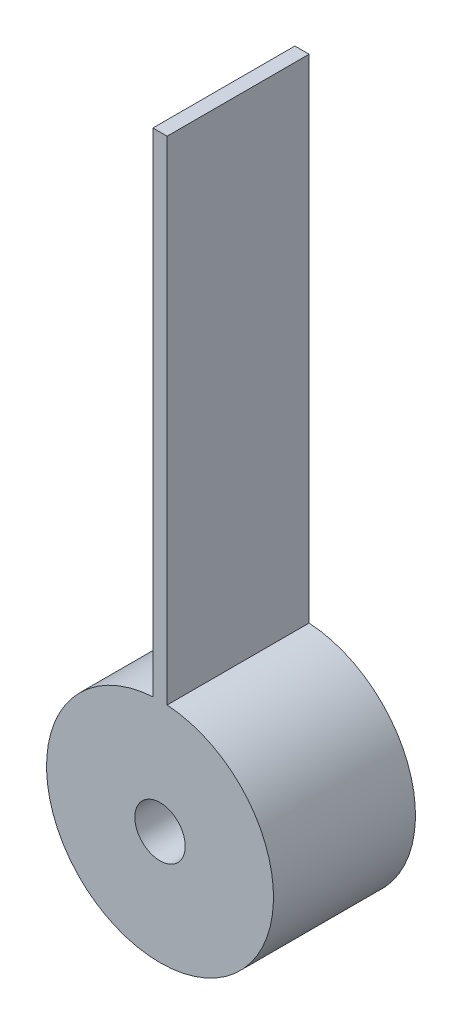
SolidWorks part; units mm, degrees
ref_plane "前视基准面" through (0, 0, 0) normal (0, 0, 1) x (1, 0, 0)
ref_plane "上视基准面" through (0, 0, 0) normal (0, 1, 0) x (1, 0, 0)
ref_plane "右视基准面" through (0, 0, 0) normal (1, 0, 0) x (0, 0, -1)
sketch "Model" plane through (0, 0, 0) normal (0, 0, 1) x (1, 0, 0)
  line L0 (98.576, 107.4567) -> (109.2328, 107.4567)
  line L1 (104.6851, 111.1897) -> (106.5119, 107.4567)
  line L2 (103.1237, 111.1897) -> (101.2969, 107.4567)
  line L3 (84.8109, 167.8456) -> (84.8109, 160.741)
  line L4 (84.8109, 160.741) -> (82.1466, 160.741)
  line L5 (84.8109, 167.8456) -> (82.1466, 167.8456)
  line L6 (87.4751, 167.8456) -> (87.4751, 160.741)
  line L7 (87.4751, 160.741) -> (90.1393, 160.741)
  line L8 (87.4751, 167.8456) -> (90.1393, 167.8456)
  line L9 (98.576, 107.0039) -> (99.0288, 107.4567)
  line L10 (98.576, 105.0101) -> (101.0225, 107.4567)
  line L11 (100.3521, 104.7925) -> (103.0163, 107.4567)
  line L12 (102.3459, 104.7925) -> (105.0101, 107.4567)
  line L13 (104.3397, 104.7925) -> (107.0039, 107.4567)
  line L14 (106.3334, 104.7925) -> (108.9977, 107.4567)
  line L15 (82.1466, 166.3381) -> (83.6541, 167.8456)
  line L16 (82.1466, 164.3443) -> (84.8109, 167.0085)
  line L17 (82.1466, 162.3506) -> (84.8109, 165.0148)
  line L18 (82.5308, 160.741) -> (84.8109, 163.021)
  line L19 (84.5246, 160.741) -> (84.8109, 161.0272)
  line L20 (87.4751, 167.679) -> (87.6416, 167.8456)
  line L21 (87.4751, 165.6852) -> (89.6354, 167.8456)
  line L22 (87.4751, 163.6914) -> (90.1393, 166.3556)
  line L23 (87.4751, 161.6977) -> (90.1393, 164.3619)
  line L24 (88.5122, 160.741) -> (90.1393, 162.3681)
  line L25 (86.143, 137.1587) -> (86.143, 178.0584)
  line L26 (86.143, 178.0584) -> (85.643, 178.0584)
  line L27 (86.143, 178.0584) -> (86.643, 178.0584)
  line L28 (85.643, 178.0584) -> (85.643, 143.3595)
  line L29 (86.643, 178.0584) -> (86.643, 143.3595)
  circle A0 centre (103.9044, 112.7851) radius 1.7761
  circle A1 centre (86.143, 135.3826) radius 7.9926
  circle A2 centre (86.143, 135.3826) radius 1.7761
  arc A3 (108.9107, 119.2638) -> (96.8478, 116.9374) centre (103.9044, 112.7851) ccw
  arc A4 (99.2234, 119.5026) -> (96.8478, 116.9374) centre (103.9044, 112.7851) ccw
  spline S0 degree 3 poles (87.8153, 127.3728) (91.6519, 129.09) (95.5025, 130.8246) (99.8156, 132.1638) (103.5377, 132.5082) (106.6862, 132.6656) (110.229, 132.3961) (113.8975, 131.1403) (117.8457, 128.7534) (121.6231, 125.4243) (125.6785, 120.5) (130.2984, 114.1306) (134.0269, 106.8865) (135.6212, 101.4647) (136.7682, 97.7963) (137.397, 94.167) (137.3579, 89.314) (136.4473, 83.5323) (133.3741, 77.6482) (129.0452, 72.2789) (125.0833, 68.3865) (121.3398, 66.1034) (117.6497, 64.9583) (113.6067, 64.0065) (108.9974, 63.4117) (104.3061, 63.3824) (99.5847, 63.6057) (95.1021, 64.1854) (90.7946, 64.9972) (86.6995, 66.6143) (83.4359, 68.3905) (80.3418, 70.0499) (76.8669, 72.541) (73.0704, 75.6567) (69.8007, 79.9865) (66.2492, 84.636) (65.3028, 91.2762) (65.851, 97.5635) (66.4795, 103.5965) (67.0332, 108.6575) (68.9157, 113.0833) (70.1566, 116.8633) (72.778, 119.1315) (74.8675, 121.1643) (77.2797, 122.3392) (80.3246, 124.2291) (84.1579, 125.8508) (87.8153, 127.3728) (91.6519, 129.09) (95.5025, 130.8246) knots -0.053528 -0.030186 -0.010705 0 0.026546 0.046329 0.060553 0.076868 0.088874 0.108295 0.128518 0.150854 0.175898 0.214483 0.256993 0.284989 0.290659 0.308876 0.334401 0.35592 0.38726 0.422471 0.449005 0.461679 0.481274 0.500786 0.517775 0.543869 0.564008 0.581536 0.604881 0.622946 0.640688 0.655045 0.670269 0.698381 0.72078 0.743531 0.77623 0.807771 0.829063 0.85826 0.875615 0.89409 0.910614 0.921398 0.933329 0.946472 0.969814 0.989295 1 1.026546 1.046329 1.060553 only from (90.5803, 128.611) to (90.5803, 128.611)
  spline S1 degree 3 poles (115.1837, 56.2408) (114.5241, 56.1179) (113.8567, 56.0082) (112.5215, 55.8179) (111.8517, 55.737) (110.5434, 55.6073) (109.9033, 55.5573) (108.6447, 55.4828) (108.0235, 55.4577) (106.1857, 55.4112) (104.9946, 55.4181) (103.3546, 55.4547) (102.8698, 55.4689) (101.8872, 55.5059) (100.7921, 55.5566) (99.6755, 55.6337) (98.6085, 55.7239) (98.1561, 55.7674) (97.2631, 55.8628) (96.3316, 55.9725) (95.4159, 56.0987) (94.4434, 56.2415) (93.9543, 56.3175) (92.9406, 56.4862) (92.4215, 56.5786) (90.8301, 56.8896) (89.7232, 57.1418) (88.1662, 57.5889) (87.7468, 57.7184) (86.9269, 57.9895) (86.5229, 58.132) (85.3284, 58.5775) (84.5556, 58.8986) (83.4175, 59.413) (83.0346, 59.5939) (82.2989, 59.9535) (81.9437, 60.133) (80.913, 60.6653) (80.2725, 61.0111) (79.4606, 61.4495) (79.2559, 61.5599) (78.8233, 61.7937) (78.5995, 61.915) (77.9066, 62.2948) (77.4162, 62.5689) (76.4534, 63.1371) (75.9786, 63.4313) (75.0881, 64.0128) (74.6624, 64.3046) (73.8303, 64.8936) (73.4251, 65.1906) (72.825, 65.6393) (72.618, 65.7956) (72.1968, 66.1174) (71.5606, 66.6089) (70.9134, 67.1296) (69.6115, 68.2164) (68.7329, 69.0016) (67.5914, 70.1427) (67.3162, 70.4273) (66.776, 71.008) (66.5177, 71.2966) (65.7738, 72.1528) (65.3192, 72.7105) (64.485, 73.7664) (64.1035, 74.266) (63.6418, 74.8733) (63.5422, 75.0045) (63.2479, 75.3919) (63.0392, 75.6663) (62.407, 76.5103) (61.9568, 77.1251) (61.0304, 78.5155) (60.5536, 79.2922) (59.8988, 80.5666) (59.6989, 80.9893) (59.3395, 81.8244) (59.1767, 82.2413) (58.7342, 83.4858) (58.4999, 84.3068) (57.9096, 86.8406) (57.7188, 88.4946) (57.5854, 90.8794) (57.5693, 91.6818) (57.5774, 93.2473) (57.6022, 94.0077) (57.687, 95.6677) (57.7543, 96.5546) (57.8769, 97.9644) (57.9284, 98.5066) (58.0824, 100.0917) (58.189, 101.1397) (58.3536, 102.7184) (58.4096, 103.2492) (58.5104, 104.1971) (58.5562, 104.6275) (58.6579, 105.5269) (58.7137, 105.9935) (58.9065, 107.4417) (59.0686, 108.4721) (59.3941, 109.9847) (59.5538, 110.6599) (59.7471, 111.3538) (59.8825, 111.812) (59.9466, 112.0191) (60.0749, 112.4173) (60.1396, 112.6104) (60.3333, 113.1724) (60.4621, 113.5239) (60.7016, 114.1601) (60.813, 114.4477) (60.9997, 114.9272) (61.0775, 115.126) (61.2975, 115.693) (61.4133, 116.0018) (61.7236, 116.8399) (61.9075, 117.3383) (62.3761, 118.4773) (62.6612, 119.1192) (63.1864, 120.0978) (63.3517, 120.3872) (63.6444, 120.8612) (63.7606, 121.0415) (63.9874, 121.3763) (64.0944, 121.5281) (64.3063, 121.8178) (64.4123, 121.9574) (64.729, 122.3615) (64.9384, 122.611) (65.5515, 123.3074) (65.9396, 123.7022) (66.6429, 124.3876) (66.9586, 124.6785) (67.3277, 125.0183) (67.4203, 125.1034) (67.5918, 125.2618) (67.6674, 125.332) (67.9406, 125.5869) (68.1629, 125.7963) (68.6066, 126.1994) (68.8052, 126.3764) (69.3151, 126.8113) (69.6423, 127.0774) (70.1779, 127.4736) (70.3521, 127.5973) (70.6838, 127.8235) (70.8449, 127.929) (71.3121, 128.2253) (71.6018, 128.3962) (72.1972, 128.7349) (72.4887, 128.8914) (72.9151, 129.1195) (73.071, 129.2025) (73.2901, 129.321) (73.363, 129.361) (73.5223, 129.4496) (73.6056, 129.4965) (73.8666, 129.6452) (74.0555, 129.7548) (74.6688, 130.1123) (75.1397, 130.3895) (75.8661, 130.7918) (76.0586, 130.8962) (76.435, 131.0958) (76.9961, 131.3868) (77.5454, 131.6549) (78.6251, 132.1655) (79.3199, 132.4722) (80.4305, 132.9491) (80.8634, 133.1311) (82.115, 133.656) (82.9267, 133.9947) (84.1792, 134.5258) (84.6324, 134.7198) (85.4087, 135.0575) (85.7398, 135.2035) (86.4805, 135.5324) (86.8904, 135.716) (87.308, 135.9031) knots 124.95846 124.95846 124.95846 124.95846 126.851625 126.851625 128.74479 128.74479 130.540216 130.540216 132.335642 132.335642 135.926493 135.926493 137.432557 137.432557 138.93862 140.758492 140.758492 142.085094 142.085094 143.411695 144.875502 144.875502 146.401689 146.401689 147.927876 147.927876 150.98025 150.98025 152.088003 152.088003 153.195757 153.195757 155.411264 155.411264 156.557338 156.557338 157.703412 157.703412 159.995561 159.995561 160.80138 160.80138 161.607198 161.607198 163.218836 163.218836 164.626323 164.626323 166.03381 166.03381 167.493852 167.493852 168.286348 168.286348 169.078843 170.663834 170.663834 173.833815 173.833815 174.840372 174.840372 175.846929 175.846929 177.860043 177.860043 179.81116 179.81116 180.359658 180.359658 181.456653 181.456653 183.521816 183.521816 185.586979 185.586979 186.519725 186.519725 187.45247 187.45247 189.317962 189.317962 193.324578 193.324578 195.476707 195.476707 197.628836 197.628836 200.317475 200.317475 202.071935 202.071935 205.580854 205.580854 207.361877 207.361877 208.763109 208.763109 210.164341 210.164341 212.966804 212.966804 214.063329 214.67253 214.67253 215.180192 215.180192 215.687854 215.687854 216.703178 216.703178 217.644549 217.644549 218.372655 218.372655 219.828867 219.828867 221.285079 221.285079 222.741291 222.741291 223.326665 223.326665 223.678609 223.678609 223.974426 223.974426 224.270244 224.270244 224.86188 224.86188 226.045151 226.045151 227.228422 227.228422 227.659654 227.659654 228.08589 228.08589 228.993858 228.993858 229.609088 229.609088 230.414166 230.414166 230.766752 230.766752 231.119337 231.119337 231.824508 231.824508 232.706509 232.706509 233.340309 233.340309 233.753263 233.753263 234.166216 234.166216 234.992124 234.992124 236.643938 236.643938 237.203236 237.203236 237.762535 238.881131 238.881131 241.118325 241.118325 242.624871 242.624871 245.637965 245.637965 247.38835 247.38835 248.685938 248.685938 250.231645 250.231645 250.231645 250.231645
  spline S2 degree 3 poles (87.308, 135.9031) (87.7349, 136.095) (88.1714, 136.2912) (89.5122, 136.8876) (90.4476, 137.2955) (92.0832, 137.9618) (92.7537, 138.2232) (94.1512, 138.731) (94.8867, 138.9802) (96.3938, 139.4303) (97.1613, 139.6331) (98.5103, 139.9236) (99.0819, 140.0274) (100.161, 140.1904) (100.6775, 140.2529) (101.7229, 140.3611) (102.2454, 140.4036) (103.0155, 140.4602) (103.2958, 140.4796) (103.8727, 140.5154) (104.167, 140.5317) (105.0677, 140.5735) (105.692, 140.5918) (106.9043, 140.594) (107.4842, 140.5826) (108.5756, 140.5255) (109.074, 140.4874) (109.9481, 140.3916) (110.3154, 140.3433) (110.9984, 140.2352) (111.3126, 140.1785) (111.9266, 140.0539) (112.2294, 139.9857) (113.1253, 139.765) (113.7056, 139.5966) (115.1371, 139.1256) (115.9653, 138.8) (117.4894, 138.1202) (118.1943, 137.7685) (119.5619, 137.0198) (120.2224, 136.6237) (122.1363, 135.3836) (123.3216, 134.4898) (125.1216, 132.9625) (125.7794, 132.3613) (126.9163, 131.2516) (127.406, 130.7466) (128.3377, 129.741) (128.7821, 129.2386) (129.6678, 128.2028) (130.1064, 127.6701) (130.8325, 126.7668) (131.1267, 126.3943) (131.7069, 125.6515) (132.5748, 124.5271) (133.4318, 123.3698) (135.1217, 121.0052) (136.2176, 119.3599) (138.2839, 115.915) (139.2525, 114.1202) (140.5148, 111.4214) (140.8841, 110.5774) (141.5213, 109.0045) (141.7971, 108.2731) (142.2986, 106.8565) (142.528, 106.1655) (142.903, 104.9965) (143.1525, 104.1971) (143.3882, 103.4296) (143.5963, 102.7519) (143.7037, 102.4035) (143.8899, 101.8015) (143.9571, 101.5833) (144.0769, 101.1792) (144.1279, 101.0036) (144.2879, 100.4289) (144.387, 100.0401) (144.6587, 98.8778) (144.8054, 98.1081) (145.1087, 96.1434) (145.2226, 94.9641) (145.3394, 92.6258) (145.3409, 91.4695) (145.2741, 89.818) (145.2438, 89.3098) (145.1731, 88.396) (145.1361, 87.9903) (145.0472, 87.1599) (144.9955, 86.7381) (144.8134, 85.4544) (144.6562, 84.5739) (144.3464, 83.2304) (144.232, 82.7825) (144.0108, 82.0058) (143.9109, 81.6795) (143.702, 81.0407) (143.5923, 80.7261) (143.2498, 79.7962) (143.0033, 79.1952) (142.2226, 77.4465) (141.6477, 76.3533) (140.7247, 74.771) (140.3947, 74.2365) (139.3932, 72.6843) (138.6936, 71.6921) (137.4505, 70.0522) (136.4479, 68.797) (135.4122, 67.6056) (134.6014, 66.7044) (134.2833, 66.3581) (133.618, 65.651) (133.2723, 65.2925) (132.1904, 64.2092) (131.4091, 63.4763) (129.9827, 62.2803) (129.3809, 61.8101) (128.2645, 61.0159) (127.3209, 60.3891) (126.2997, 59.8092) (125.4513, 59.3686) (125.0925, 59.194) (124.3891, 58.8736) (124.0422, 58.7261) (123.0192, 58.3157) (122.3612, 58.085) (121.2805, 57.7374) (120.8432, 57.6067) (120.1735, 57.4154) (119.9309, 57.3482) (119.4545, 57.2187) (118.7358, 57.0273) (117.2527, 56.6596) (115.974, 56.3879) (115.1837, 56.2408) knots 0.006287 0.006287 0.006287 0.006287 1.587442 1.587442 4.749752 4.749752 6.84188 6.84188 8.934008 8.934008 10.910356 10.910356 12.246423 12.246423 13.58249 13.58249 15.083565 15.083565 15.937851 15.937851 16.792137 16.792137 18.500708 18.500708 19.989565 19.989565 21.164064 21.164064 21.984167 21.984167 22.659467 22.659467 23.334768 23.334768 24.685369 24.685369 26.766115 26.766115 28.697415 28.697415 30.628714 30.628714 34.491313 34.491313 36.870126 36.870126 38.776962 38.776962 40.683798 40.683798 42.73982 42.73982 44.22523 44.22523 45.71064 48.681459 48.681459 54.623098 54.623098 60.564737 60.564737 63.20019 63.20019 65.391996 65.391996 67.583803 67.583803 69.209371 70.253118 70.253118 71.606825 71.606825 72.274834 72.274834 72.739414 72.739414 73.717089 73.717089 75.672437 75.672437 78.759863 78.759863 81.84729 81.84729 83.23248 83.23248 84.354978 84.354978 85.477476 85.477476 87.722471 87.722471 88.827498 88.827498 89.622298 89.622298 90.417099 90.417099 92.0067 92.0067 95.185902 95.185902 96.892902 96.892902 100.306902 100.306902 102.759993 104.930632 104.930632 106.339376 106.339376 107.74812 107.74812 110.565607 110.565607 112.427206 112.427206 113.81362 115.061892 115.061892 115.921993 115.921993 116.782095 116.782095 118.502298 118.502298 119.7428 119.7428 120.479533 120.479533 121.216266 122.689732 124.95846 124.95846 124.95846 124.95846
  text T0 "ω" font "TIMES NEW ROMAN" height 2.5
  text T1 "O" font "TIMES NEW ROMAN" height 2
  text T2 "B" font "TIMES NEW ROMAN" height 2
  dimension "D1" = 0.5
  dimension "D2" = 0.5
extrude "凸台-拉伸1" add sketch "Model" along normal blind 10 contours A1 L25 L26 L28 | A1 L29 L27 L25 | A1 S1 A2 L25 | A2 S2 A1 L25 | S2 A2 S1 A1
